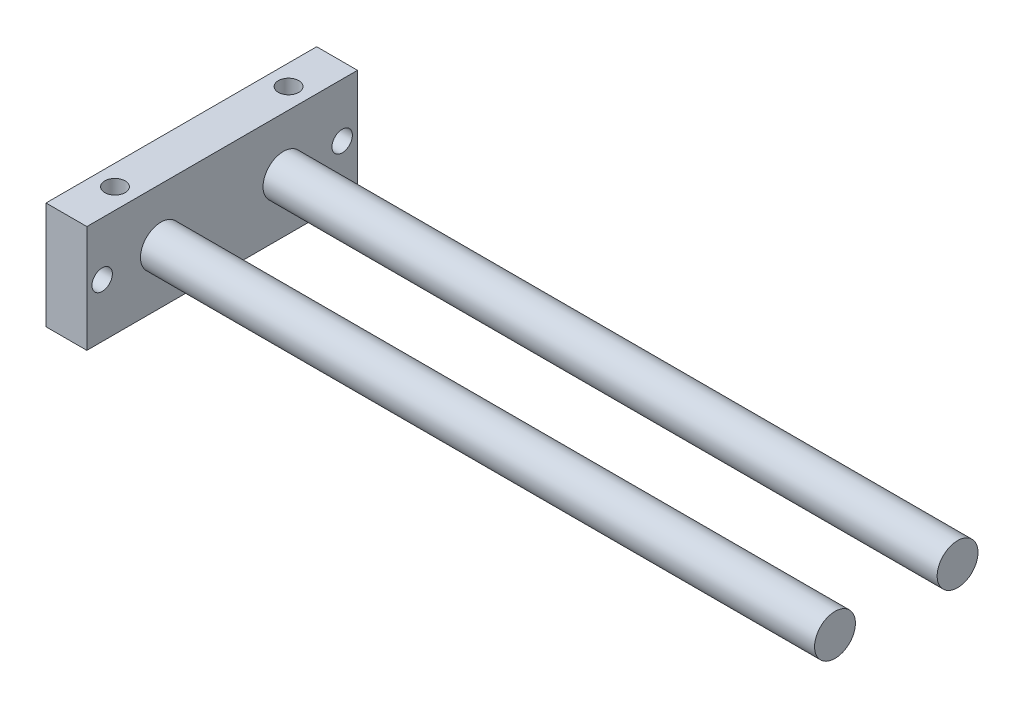
SolidWorks part; units mm, degrees
ref_plane "前视基准面" through (0, 0, 0) normal (0, 0, 1) x (1, 0, 0)
ref_plane "上视基准面" through (0, 0, 0) normal (0, 1, 0) x (1, 0, 0)
ref_plane "右视基准面" through (0, 0, 0) normal (1, 0, 0) x (0, 0, -1)
sketch "草图1" plane through (0, 0, 0) normal (1, 0, 0) x (0, 0, -1)
  line L0 (26.5, 0) -> (26.5, 21) construction
  line L1 (0, 0) -> (53, 0)
  line L2 (0, 0) -> (0, 21)
  line L3 (0, 21) -> (53, 21)
  line L4 (53, 0) -> (53, 21)
  circle A0 centre (50, 10.5) radius 2
  circle A1 centre (3, 10.5) radius 2
  dimension "D3" = 4
  dimension "D4" = 47
  dimension "D1" = 53
  dimension "D2" = 21
extrude "凸台-拉伸1" add sketch "草图1" along normal blind 8
sketch "草图2" plane through (0, 0, 0) normal (-1, 0, 0) x (0, 0, 1)
  line L0 (-26.5, 21) -> (-26.5, 0) construction
  line L1 (-53, 21) -> (0, 21) construction
  line L2 (0, 0) -> (-53, 0) construction
  circle A0 centre (-14.5, 10.5) radius 4
  circle A1 centre (-38.5, 10.5) radius 4
  dimension "D1" = 8
  dimension "D2" = 24
extrude "切除-拉伸1" cut sketch "草图2" against normal blind 5
sketch "草图3" plane through (8, 0, 0) normal (1, 0, 0) x (0, 0, -1)
  line L0 (26.5, 21) -> (26.5, 0) construction
  line L1 (53, 21) -> (0, 21) construction
  line L2 (0, 0) -> (53, 0) construction
  circle A0 centre (38.5, 10.5) radius 4
  circle A1 centre (14.5, 10.5) radius 4
  point P8 (26.5, 10.5)
  dimension "D1" = 8
  dimension "D2" = 24
extrude "凸台-拉伸2" add sketch "草图3" along normal blind 132
sketch "草图4" plane through (0, 21, 0) normal (0, 1, 0) x (1, 0, 0)
  line L0 (8, 26.5) -> (0, 26.5) construction
  line L1 (8, 53) -> (8, 0) construction
  line L2 (0, 53) -> (0, 0) construction
  circle A0 centre (4, 43.5) radius 2
  circle A1 centre (4, 9.5) radius 2
  point P6 (4, 26.5)
  dimension "D1" = 34
  dimension "D2" = 4
extrude "切除-拉伸2" cut sketch "草图4" against normal blind 5
